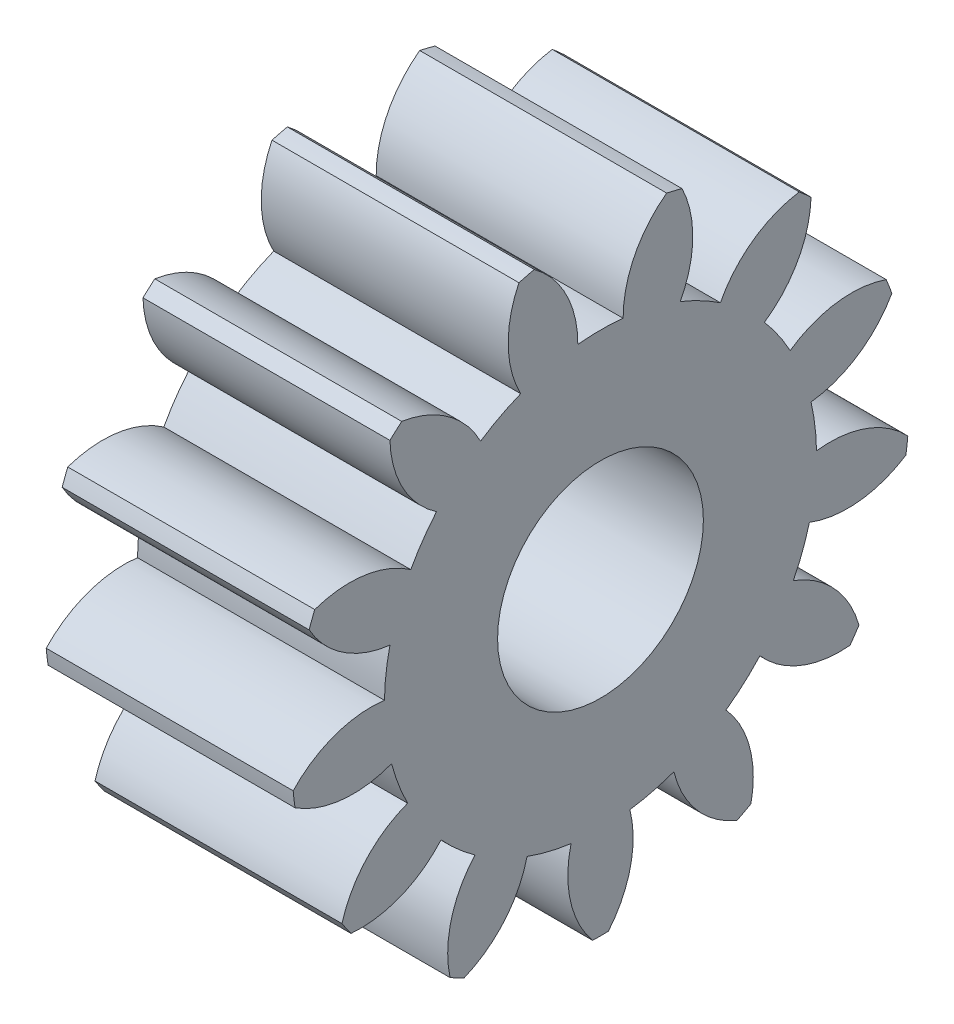
SolidWorks part; units mm, degrees
ref_plane "Plane1" through (0, 0, 0) normal (0, 0, 1) x (1, 0, 0)
ref_plane "Plane2" through (0, 0, 0) normal (0, 1, 0) x (1, 0, 0)
ref_plane "Plane3" through (0, 0, 0) normal (1, 0, 0) x (0, 0, -1)
other "Configuration Table"
sketch "HoldingSke" plane through (0, 0, 0) normal (0, 1, 0) x (1, 0, 0)
  line L0 (0, 0) -> (0.9744, -0.225)
  line L1 (-15, 0) -> (100, 0) construction
  line L2 (0, 0) -> (-2.1039, 2.3779)
  line L3 (0, 0) -> (-11.863, 4.5341)
  line L4 (0, 0) -> (8.4147, 1.9427)
  line L5 (0, 0) -> (-46.8476, -17.4728)
  line L6 (0, 0) -> (-4.9738, -3.3558)
  line L7 (-2.1039, 2.3779) -> (8.6586, 51.2059)
  line L8 (-76.2, 54.61) -> (-75.3, 54.61)
  line L9 (-71.009, 38.7566) -> (-53.1078, 45.2721)
  line L10 (-76.2, 71.12) -> (104.1128, 71.12)
  line L11 (0, 0) -> (-6, 0)
  line L12 (-76.2, 101.6) -> (-76.162, 101.6)
  line L13 (24.9733, 27.94) -> (52.9518, 28.4284)
  line L14 (24.9733, 27.94) -> (24.9743, 27.94)
  line L15 (24.9733, 27.94) -> (100.4006, 29.5858)
  line L16 (-63.627, -1) -> (-12.827, -1)
  circle A0 centre (0, 0) radius 2.5
  circle A1 centre (0, 0) radius 5.249
  circle A2 centre (0, 0) radius 37.5
  circle A3 centre (0, 0) radius 2.5
  dimension "MHD" = 10.498
  dimension "Hub_dia" = 75
  dimension "Bore" = 5
  dimension "MBD" = 5
  dimension "Num_teeth" = 13
  dimension "Pitch" = 1
  dimension "Overall_len" = 50
  dimension "Show_teeth" = 13
  dimension "Thickness" = 6
  dimension "OAL" = 50.0001
  dimension "T_dim" = 0.9
  dimension "Ap" = 20
  dimension "H" = 19.05
  dimension "Pitch_radius" = 180.3128
  dimension "Width" = 6
  dimension "Backlash" = 0.038
  dimension "Addendum_fac" = 1
  dimension "Dedendum_fac" = 1.25
  dimension "Clearance_fac" = 0.25
  dimension "Dedendum_add" = 0.001
  dimension "Module" = 1
sketch "BasProSke" plane through (0, 0, 0) normal (0, 1, 0) x (1, 0, 0)
  line L0 (-10, 0) -> (60, 0) construction
  line L1 (0, 0) -> (0, 7.5)
  line L2 (0, 0) -> (6, 0)
  line L3 (6, 0) -> (6, 7.5)
  line L4 (6, 7.5) -> (0, 7.5)
  dimension "Thickness" = 6
  dimension "Diameter" = 15
revolve "Base-Revolve" add sketch "BasProSke" angle 360 about L0
sketch "TooCutSke" plane through (0, 0, 0) normal (1, 0, 0) x (0, 0, -1)
  line L1 (0, 0) -> (0, 107) construction
  line L2 (0, 0) -> (-0.8499, 6.4442) construction
  line L3 (0, 0) -> (-3.0921, 12.5452) construction
  line L4 (-0.8499, 6.4442) -> (-1.5461, 6.2726) construction
  arc A0 (0.5505, 5.2201) -> (-0.5505, 5.2201) centre (0, 0) ccw
  arc A1 (1.6352, 7.3456) -> (-1.6352, 7.3456) centre (0, 0) ccw
  circle A2 centre (0, 0) radius 6.5 construction
  circle A3 centre (0, 0) radius 6.108 construction
  arc A4 (-0.5505, 5.2201) -> (-1.6352, 7.3456) centre (-3.1505, 5.2328) ccw
  arc A5 (1.6352, 7.3456) -> (0.5505, 5.2201) centre (3.1505, 5.2328) ccw
  dimension "Root_dia" = 10.498
  dimension "Overcut_dia" = 15.0508
  dimension "Pitch_dia" = 13
  dimension "Base_dia" = 12.216
  dimension "Flank_rad" = 2.6
  dimension "Half_ang" = 13.846
  dimension "Half_CT" = 0.717
extrude "ToothCut" cut sketch "TooCutSke" along normal through all
fillet "Breaks" [suppressed] radius 0.02
fillet "RootFillets" [suppressed] radius 0.251
pattern_circular "TeethCuts" count 13 every 27.692 about axis through (-10, 0, 0) along (1, 0, 0) of "ToothCut", "RootFillets", "Breaks"
sketch "HubNeaOneSke" plane through (0, 0, 0) normal (-1, 0, 0) x (0, 0, 1)
  circle A0 centre (0, 0) radius 5.249
  dimension "Diameter" = 10.498
extrude "HubNearOne" [suppressed] add sketch "HubNeaOneSke" along normal blind 44.0001
sketch "HubNeaBotSke" plane through (0, 0, 0) normal (-1, 0, 0) x (0, 0, 1)
  circle A0 centre (0, 0) radius 5.249
  dimension "Diameter" = 10.498
extrude "HubNearBoth" [suppressed] add sketch "HubNeaBotSke" along normal blind 22
ref_plane "FarPln" through (6, 0, 0) normal (1, 0, 0) x (0, 0, -1)
sketch "HubFarSke" plane through (6, 0, 0) normal (1, 0, 0) x (0, 0, -1)
  circle A0 centre (0, 0) radius 5.249
  dimension "Diameter" = 10.498
extrude "HubFar" [suppressed] add sketch "HubFarSke" along normal blind 22
sketch "BorSke" plane through (0, 0, 0) normal (1, 0, 0) x (0, 0, -1)
  circle A0 centre (0, 0) radius 2.5
  dimension "Diameter" = 5
extrude "Bore" cut sketch "BorSke" along normal mid plane 100.0001
sketch "KeySke" plane through (0, 0, 0) normal (1, 0, 0) x (0, 0, -1)
  line L0 (-1, 0) -> (-1, 3.4)
  line L1 (-1, 3.4) -> (1, 3.4)
  line L2 (1, 3.4) -> (1, 0)
  line L3 (0, 0) -> (0, 34) construction
  line L4 (-1, 0) -> (1, 0)
  dimension "Offset" = 3.4
  dimension "Width" = 2
extrude "Keyway" [suppressed] cut sketch "KeySke" along normal mid plane 100.0001
pattern_circular "Keyway2" [suppressed] count 2 every 90 about axis through (-10, 0, 0) along (1, 0, 0)
equation "' \"Module@HoldingSke\" = 6.35"
equation "' \"Num_teeth@HoldingSke\" = 12"
equation "' \"Ap@HoldingSke\" =  20"
equation "' \"Ap@HoldingSke\" = 20"
equation "' \"Width@HoldingSke\" = 0.5 * 25.4"
equation "' \"Hub_dia@HoldingSke\"= 1 * 25.4"
equation "' \"Hub_dia@HoldingSke\" = 1 * 25.4"
equation "' \"Overall_len@HoldingSke\" = 1.0 * 25.4"
equation "' \"Bore@HoldingSke\" = 0.75 * 25.4"
equation "' \"T_dim@HoldingSke\" = 0.1 * 25.4"
equation "' \"Width@KeySke\" = 0.25 * 25.4"
equation "' \"Show_teeth@HoldingSke\" = 13"
equation "' \"Backlash@HoldingSke\" = 0.009 * 25.4"
equation "' \"Addendum_fac@HoldingSke\" = 1.0"
equation "' \"Dedendum_fac@HoldingSke\" = 1.25"
equation "' \"Dedendum_add@HoldingSke\" = 0.00005 * 25.4"
equation "' \"Clearance_fac@HoldingSke\" = 0.25"
equation "\"Pitch@HoldingSke\" = 1 / \"Module@HoldingSke\""
equation "\"Overcut_dia@TooCutSke\" = (\"Num_teeth@HoldingSke\" + 2 * \"Addendum_fac@HoldingSke\") / \"Pitch@HoldingSke\" + 0.002 * 25.4"
equation "\"Pitch_dia@TooCutSke\" = \"Num_teeth@HoldingSke\" / \"Pitch@HoldingSke\""
equation "\"Base_dia@TooCutSke\" = \"Num_teeth@HoldingSke\" / \"Pitch@HoldingSke\" * cos((\"Ap@HoldingSke\"  * 3.14159265 / 180))"
equation "\"Root_dia@TooCutSke\" = (\"Num_teeth@HoldingSke\" + 2) / \"Pitch@HoldingSke\" - 2 * (\"Addendum_fac@HoldingSke\" + \"Dedendum_fac@HoldingSke\") / \"Pitch@HoldingSke\" - \"Dedendum_add@HoldingSke\" * 2"
equation "\"Half_ang@TooCutSke\" = 180 / \"Num_teeth@HoldingSke\""
equation "\"Half_CT@TooCutSke\" = \"Num_teeth@HoldingSke\" / \"Pitch@HoldingSke\" * sin((3.14159265 / 2 / \"Num_teeth@HoldingSke\")) / 2 - 7 * \"Backlash@HoldingSke\" / 4"
equation "\"Flank_rad@TooCutSke\" = \"Num_teeth@HoldingSke\" / \"Pitch@HoldingSke\" / 5"
equation "\"Radius@RootFillets\" = \"Clearance_fac@HoldingSke\" / \"Pitch@HoldingSke\" + \"Dedendum_add@HoldingSke\""
equation "\"Break_rad@Breaks\" = 0.02 / \"Pitch@HoldingSke\""
equation "\"Thickness@HoldingSke\" = \"Width@HoldingSke\""
equation "\"OAL@HoldingSke\" = \"Thickness@HoldingSke\""
equation "\"MHD@HoldingSke\" = (\"Num_teeth@HoldingSke\" + 2) / \"Pitch@HoldingSke\" - 2 * (\"Addendum_fac@HoldingSke\" + \"Dedendum_fac@HoldingSke\")  / \"Pitch@HoldingSke\" - \"Dedendum_add@HoldingSke\" * 2"
equation "\"MBD@HoldingSke\" = (\"Num_teeth@HoldingSke\" + 2) / \"Pitch@HoldingSke\" - 2 * (\"Addendum_fac@HoldingSke\" + \"Dedendum_fac@HoldingSke\")  / \"Pitch@HoldingSke\" - \"Dedendum_add@HoldingSke\" * 2 - 0.002 * 25.4"
equation "\"MHD@HoldingSke\" = ((sgn( \"MHD@HoldingSke\" - \"Hub_dia@HoldingSke\" )-1)*( \"MHD@HoldingSke\" - \"Hub_dia@HoldingSke\" ))/-2+ \"Hub_dia@HoldingSke\""
equation "\"MBD@HoldingSke\" = ((sgn( \"MBD@HoldingSke\" - \"Bore@HoldingSke\" )-1)*( \"MBD@HoldingSke\" - \"Bore@HoldingSke\" ))/-2+ \"Bore@HoldingSke\""
equation "\"OAL@HoldingSke\" = ((sgn( \"OAL@HoldingSke\" - \"Overall_len@HoldingSke\" )+1)*( \"OAL@HoldingSke\" - \"Overall_len@HoldingSke\" ))/2 + \"Overall_len@HoldingSke\" + 0.000002 * 25.4"
equation "\"Num_teeth@TeethCuts\" = int( \"Show_teeth@HoldingSke\" ) + 1"
equation "\"Num_teeth@TeethCuts\" = ((sgn( \"Num_teeth@TeethCuts\" - \"Num_teeth@HoldingSke\" )-1)*( \"Num_teeth@TeethCuts\" - \"Num_teeth@HoldingSke\" ))/-2+ \"Num_teeth@HoldingSke\""
equation "\"Num_teeth@TeethCuts\" = ((sgn( \"Num_teeth@TeethCuts\" - 2.0)+1)*( \"Num_teeth@TeethCuts\" - 2.0))/2 +2.0"
equation "\"Angle@TeethCuts\" = 360.0 / \"Num_teeth@HoldingSke\""
equation "\"Diameter@BasProSke\" = (\"Num_teeth@HoldingSke\" + 2 * \"Addendum_fac@HoldingSke\") / \"Pitch@HoldingSke\""
equation "\"Thickness@BasProSke\"  = \"Thickness@HoldingSke\""
equation "' \"Fillet_rad@BasProSke\" =  \"Thickness@HoldingSke\" * 0.05"
equation "' \"Fillet_rad@BasProSke\" = \"Thickness@HoldingSke\" * 0.05"
equation "\"MHD@HoldingSke\" = ((sgn( \"MHD@HoldingSke\" - \"Root_dia@TooCutSke\" )-1)*( \"MHD@HoldingSke\" - \"Root_dia@TooCutSke\" ))/-2+ \"Root_dia@TooCutSke\""
equation "\"Diameter@HubNeaOneSke\" = \"MHD@HoldingSke\""
equation "\"Length@HubNearOne\" = \"OAL@HoldingSke\" - \"Thickness@BasProSke\""
equation "\"Diameter@HubNeaBotSke\" = \"MHD@HoldingSke\""
equation "\"Length@HubNearBoth\" = ( \"OAL@HoldingSke\" - \"Thickness@BasProSke\" ) / 2.0"
equation "\"Thickness@FarPln\" = \"Thickness@BasProSke\""
equation "\"Diameter@HubFarSke\" = \"MHD@HoldingSke\""
equation "\"Length@HubFar\" = ( \"OAL@HoldingSke\" - \"Thickness@BasProSke\" ) / 2.0"
equation "\"Diameter@BorSke\" = \"MBD@HoldingSke\""
equation "\"D1@Bore\" = \"OAL@HoldingSke\" * 2.0"
equation "\"D1@Keyway\" = \"OAL@HoldingSke\" * 2.0"
equation "\"Offset@KeySke\" = \"T_dim@HoldingSke\" + \"MBD@HoldingSke\" / 2.0"
